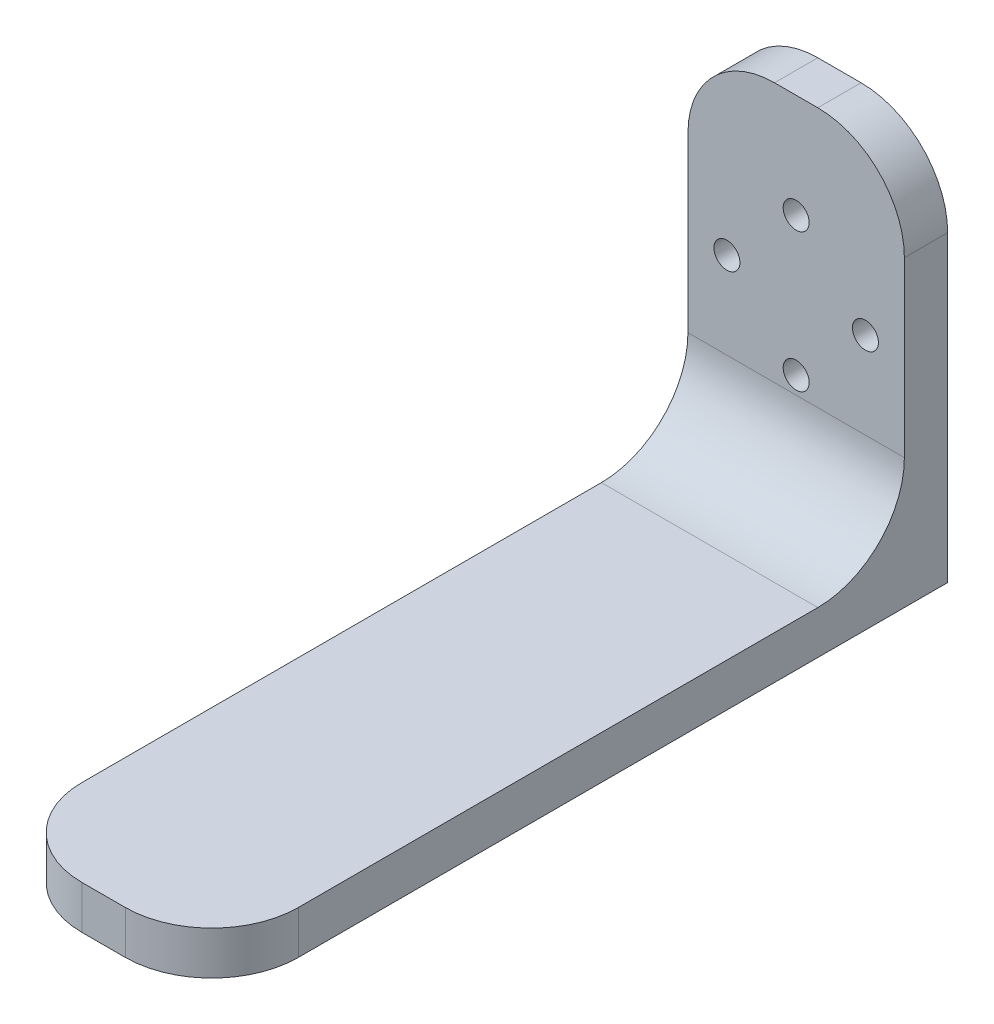
SolidWorks part; units mm, degrees
ref_plane "前视基准面" through (0, 0, 0) normal (0, 0, 1) x (1, 0, 0)
ref_plane "上视基准面" through (0, 0, 0) normal (0, 1, 0) x (1, 0, 0)
ref_plane "右视基准面" through (0, 0, 0) normal (1, 0, 0) x (0, 0, -1)
sketch "草图1" plane through (0, 0, 0) normal (0, 0, 1) x (1, 0, 0)
  line L1 (12.5, -20) -> (-12.5, -20)
  line L2 (12.5, -20) -> (12.5, 20)
  line L3 (12.5, 20) -> (-12.5, 20)
  line L4 (-12.5, -20) -> (-12.5, 20)
  line L5 (0, 20) -> (0, -20) construction
  line L6 (12.5, 0) -> (-12.5, 0) construction
  circle A0 centre (0, 0) radius 8 construction
  circle A1 centre (0, 8) radius 1.5
  circle A2 centre (8, 0) radius 1.5
  circle A3 centre (0, -8) radius 1.5
  circle A4 centre (-8, 0) radius 1.5
  point P0 (0, 0)
  point P20 (0, 0)
  dimension "D1" = 16
  dimension "D2" = 3
  dimension "D4" = 25
  dimension "D5" = 40
  dimension "D3" = 4
extrude "凸台-拉伸1" add sketch "草图1" along normal blind 5
sketch "草图2" plane through (0, -20, 0) normal (0, -1, 0) x (1, 0, 0)
  line L0 (12.5, 5) -> (12.5, 0) construction
  line L1 (-12.5, 0) -> (12.5, 0)
  line L2 (-12.5, 0) -> (-12.5, 85)
  line L3 (-12.5, 85) -> (12.5, 85)
  line L4 (12.5, 0) -> (12.5, 85)
  dimension "D1" = 85
extrude "凸台-拉伸2" add sketch "草图2" along normal blind 5
fillet "圆角1" radius 10 5 edges at (12.5, 20, 2.5) (-12.5, 20, 2.5) (12.5, -22.5, 85) (-12.5, -22.5, 85) (0, -20, 5)
